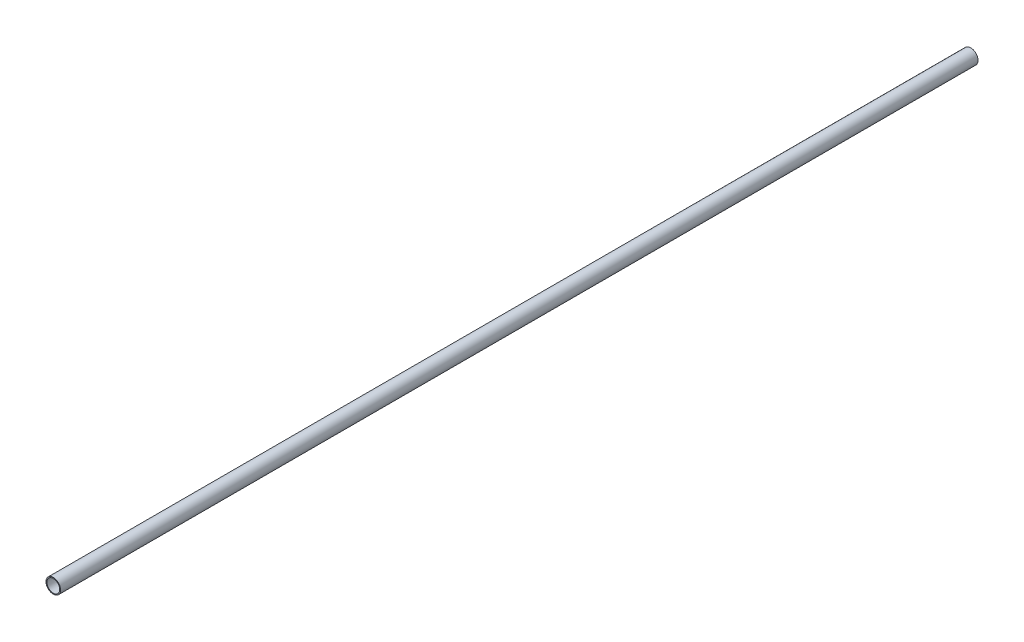
SolidWorks part; units mm, degrees
ref_plane "Front Plane" through (0, 0, 0) normal (0, 0, 1) x (1, 0, 0)
ref_plane "Top Plane" through (0, 0, 0) normal (0, 1, 0) x (1, 0, 0)
ref_plane "Right Plane" through (0, 0, 0) normal (1, 0, 0) x (0, 0, -1)
sketch "Sketch1" plane through (0, 0, 0) normal (0, 0, 1) x (1, 0, 0)
  circle A0 centre (155.331, 335.8496) radius 7.95
  circle A1 centre (155.331, 335.8496) radius 6.95
  dimension "D1" = 15.9
  dimension "D2" = 1
extrude "Boss-Extrude1" add sketch "Sketch1" along normal blind 1000
ref_plane "Plane1" through (0, 0, 500) normal (0, 0, -1) x (-1, 0, 0)
